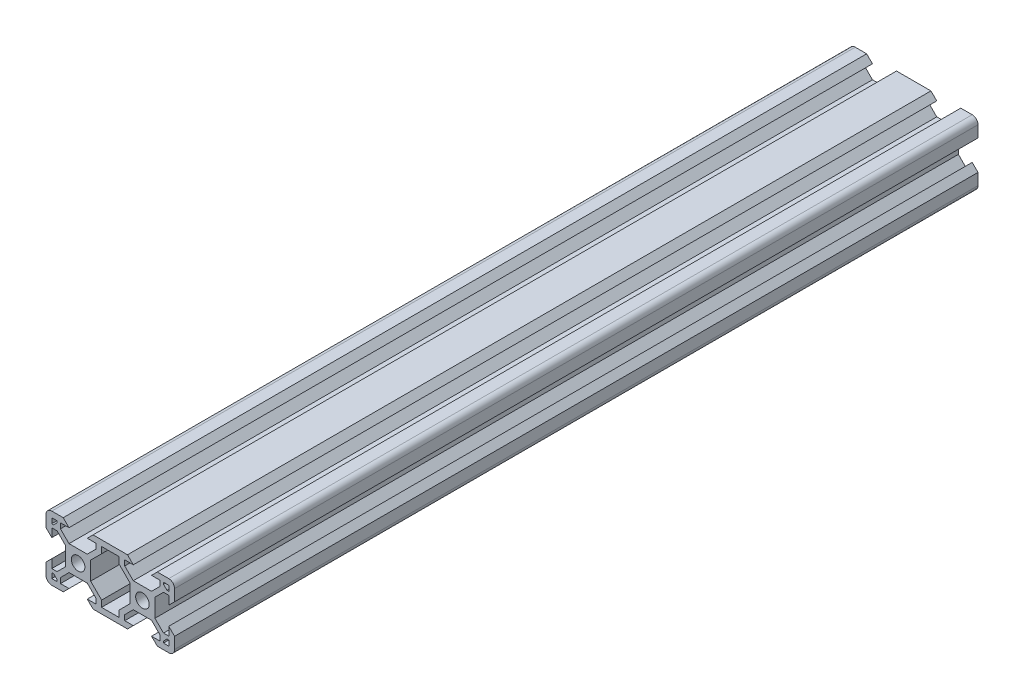
SolidWorks part; units mm, degrees
material "5052-H38, Barre (SS)"
ref_plane "Plan de face" through (0, 0, 0) normal (0, 0, 1) x (1, 0, 0)
ref_plane "Plan de dessus" through (0, 0, 0) normal (0, 1, 0) x (1, 0, 0)
ref_plane "Plan de droite" through (0, 0, 0) normal (1, 0, 0) x (0, 0, -1)
sketch "Esquisse1" plane through (0, 0, 0) normal (0, 0, 1) x (1, 0, 0)
  line L0 (0, 0) -> (0, 10) construction
  line L1 (0, 0) -> (-20, 0) construction
  line L2 (-10, 0) -> (-20, 10) construction
  line L3 (-10, 3.9007) -> (-12.84, 3.9007)
  line L4 (-12.84, 3.9007) -> (-15.4993, 6.56)
  line L5 (-15.4993, 6.56) -> (-15.4993, 8.2)
  line L6 (-15.4993, 8.2) -> (-12.84, 8.2)
  line L7 (-12.84, 8.2) -> (-14.64, 10)
  line L8 (-14.64, 10) -> (-18.2, 10)
  line L9 (-10, 0) -> (-10, 10) construction
  line L10 (-20, 4.64) -> (-20, 8.2)
  line L11 (-18.2, 2.84) -> (-20, 4.64)
  line L12 (-18.2, 5.4993) -> (-18.2, 2.84)
  line L13 (-16.56, 5.4993) -> (-18.2, 5.4993)
  line L14 (-13.9007, 2.84) -> (-16.56, 5.4993)
  line L15 (-13.9007, 0) -> (-13.9007, 2.84)
  line L16 (-10, -3.9007) -> (-12.84, -3.9007)
  line L17 (-12.84, -3.9007) -> (-15.4993, -6.56)
  line L18 (-15.4993, -6.56) -> (-15.4993, -8.2)
  line L19 (-15.4993, -8.2) -> (-12.84, -8.2)
  line L20 (-12.84, -8.2) -> (-14.64, -10)
  line L21 (-14.64, -10) -> (-18.2, -10)
  line L22 (-20, -4.64) -> (-20, -8.2)
  line L23 (-18.2, -2.84) -> (-20, -4.64)
  line L24 (-18.2, -5.4993) -> (-18.2, -2.84)
  line L25 (-16.56, -5.4993) -> (-18.2, -5.4993)
  line L26 (-13.9007, -2.84) -> (-16.56, -5.4993)
  line L27 (-13.9007, 0) -> (-13.9007, -2.84)
  line L28 (-10, 0) -> (0, 10) construction
  line L29 (-10, 3.9007) -> (-7.16, 3.9007)
  line L30 (-7.16, 3.9007) -> (-4.5007, 6.56)
  line L31 (-4.5007, 6.56) -> (-4.5007, 8.2)
  line L32 (-4.5007, 8.2) -> (-7.16, 8.2)
  line L33 (-7.16, 8.2) -> (-5.36, 10)
  line L34 (-7.16, -8.2) -> (-5.36, -10)
  line L35 (-4.5007, -8.2) -> (-7.16, -8.2)
  line L36 (-4.5007, -6.56) -> (-4.5007, -8.2)
  line L37 (-7.16, -3.9007) -> (-4.5007, -6.56)
  line L38 (-10, -3.9007) -> (-7.16, -3.9007)
  line L39 (-5.36, 10) -> (5.36, 10)
  line L40 (-5.36, -10) -> (5.36, -10)
  line L41 (-2.7, 8.2) -> (-2.7, 6.2393)
  line L42 (-2.7, 6.2393) -> (-6.0993, 2.84)
  line L43 (-2.7, 8.2) -> (2.7, 8.2)
  line L44 (-6.0993, 2.84) -> (-6.0993, -2.84)
  line L45 (-7.16, 3.9007) -> (-6.0993, 2.84) construction
  line L46 (-2.7, -8.2) -> (2.7, -8.2)
  line L47 (-2.7, -8.2) -> (-2.7, -6.2393)
  line L48 (-2.7, -6.2393) -> (-6.0993, -2.84)
  line L49 (-18.2, 8.2) -> (-18.2, 6.5693)
  line L50 (-18.2, 6.5693) -> (-17.63, 6.5693)
  line L51 (-17.63, 6.5693) -> (-16.5693, 7.63)
  line L52 (-16.5693, 7.63) -> (-16.5693, 8.2)
  line L53 (-16.5693, 8.2) -> (-18.2, 8.2)
  line L54 (-18.2, -6.5693) -> (-17.63, -6.5693)
  line L55 (-18.2, -8.2) -> (-18.2, -6.5693)
  line L56 (-16.5693, -8.2) -> (-18.2, -8.2)
  line L57 (-16.5693, -7.63) -> (-16.5693, -8.2)
  line L58 (-17.63, -6.5693) -> (-16.5693, -7.63)
  line L59 (18.2, 6.5693) -> (17.63, 6.5693)
  line L60 (18.2, 8.2) -> (18.2, 6.5693)
  line L61 (16.5693, 8.2) -> (18.2, 8.2)
  line L62 (16.5693, 7.63) -> (16.5693, 8.2)
  line L63 (17.63, 6.5693) -> (16.5693, 7.63)
  line L64 (18.2, -6.5693) -> (17.63, -6.5693)
  line L65 (18.2, -8.2) -> (18.2, -6.5693)
  line L66 (16.5693, -8.2) -> (18.2, -8.2)
  line L67 (16.5693, -7.63) -> (16.5693, -8.2)
  line L68 (17.63, -6.5693) -> (16.5693, -7.63)
  line L69 (2.7, 8.2) -> (2.7, 6.2393)
  line L70 (2.7, 6.2393) -> (6.0993, 2.84)
  line L71 (6.0993, 2.84) -> (6.0993, -2.84)
  line L72 (2.7, -6.2393) -> (6.0993, -2.84)
  line L73 (2.7, -8.2) -> (2.7, -6.2393)
  line L74 (7.16, -8.2) -> (5.36, -10)
  line L75 (4.5007, -8.2) -> (7.16, -8.2)
  line L76 (4.5007, -6.56) -> (4.5007, -8.2)
  line L77 (7.16, -3.9007) -> (4.5007, -6.56)
  line L78 (10, -3.9007) -> (7.16, -3.9007)
  line L79 (10, -3.9007) -> (12.84, -3.9007)
  line L80 (12.84, -3.9007) -> (15.4993, -6.56)
  line L81 (15.4993, -6.56) -> (15.4993, -8.2)
  line L82 (15.4993, -8.2) -> (12.84, -8.2)
  line L83 (12.84, -8.2) -> (14.64, -10)
  line L84 (14.64, -10) -> (18.2, -10)
  line L85 (20, -4.64) -> (20, -8.2)
  line L86 (18.2, -2.84) -> (20, -4.64)
  line L87 (18.2, -5.4993) -> (18.2, -2.84)
  line L88 (16.56, -5.4993) -> (18.2, -5.4993)
  line L89 (13.9007, -2.84) -> (16.56, -5.4993)
  line L90 (13.9007, 0) -> (13.9007, -2.84)
  line L91 (13.9007, 0) -> (13.9007, 2.84)
  line L92 (13.9007, 2.84) -> (16.56, 5.4993)
  line L93 (16.56, 5.4993) -> (18.2, 5.4993)
  line L94 (18.2, 5.4993) -> (18.2, 2.84)
  line L95 (18.2, 2.84) -> (20, 4.64)
  line L96 (20, 4.64) -> (20, 8.2)
  line L97 (14.64, 10) -> (18.2, 10)
  line L98 (12.84, 8.2) -> (14.64, 10)
  line L99 (15.4993, 8.2) -> (12.84, 8.2)
  line L100 (15.4993, 6.56) -> (15.4993, 8.2)
  line L101 (12.84, 3.9007) -> (15.4993, 6.56)
  line L102 (10, 3.9007) -> (12.84, 3.9007)
  line L103 (10, 3.9007) -> (7.16, 3.9007)
  line L104 (7.16, 3.9007) -> (4.5007, 6.56)
  line L105 (4.5007, 6.56) -> (4.5007, 8.2)
  line L106 (4.5007, 8.2) -> (7.16, 8.2)
  line L107 (7.16, 8.2) -> (5.36, 10)
  circle A0 centre (-10, 0) radius 2.1
  arc A1 (-18.2, 10) -> (-20, 8.2) centre (-18.2, 8.2) ccw
  arc A2 (-20, -8.2) -> (-18.2, -10) centre (-18.2, -8.2) ccw
  circle A3 centre (10, 0) radius 2.1
  arc A4 (20, -8.2) -> (18.2, -10) centre (18.2, -8.2) cw
  arc A5 (18.2, 10) -> (20, 8.2) centre (18.2, 8.2) cw
  point P57 (-6.0993, 0)
  point P61 (-17.0997, 7.0997)
  point P80 (0, 8.2)
  point P85 (0, -8.2)
  point P86 (0, -10)
  dimension "D3" = 4.2
  dimension "D2" = 20
  dimension "D4" = 5.68
  dimension "D5" = 1.5
  dimension "D6" = 1.8
  dimension "D7" = 1.64
  dimension "D11" = 5.4
  dimension "D12" = 1.07
  dimension "D8" = 2
  dimension "D9" = 2
  dimension "D10" = 2
extrude "Boss.-Extru.1" add sketch "Esquisse1" along normal mid plane 250
